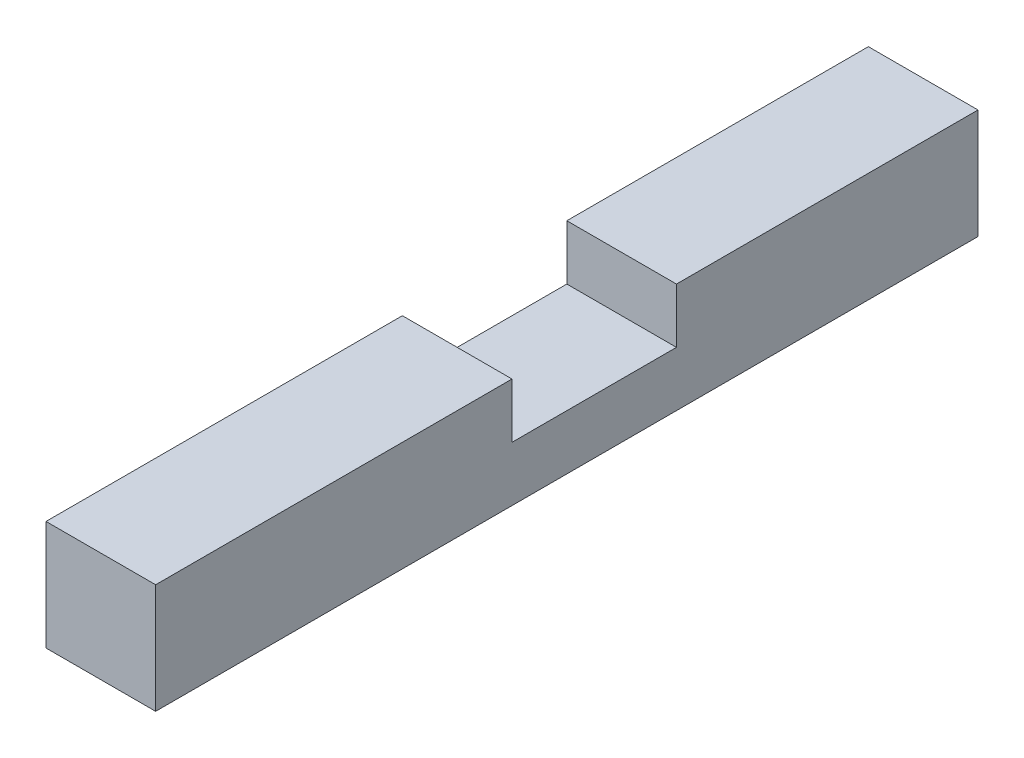
SolidWorks part; units mm, degrees
ref_plane "前基準面" through (0, 0, 0) normal (0, 0, 1) x (1, 0, 0)
ref_plane "上基準面" through (0, 0, 0) normal (0, 1, 0) x (1, 0, 0)
ref_plane "右基準面" through (0, 0, 0) normal (1, 0, 0) x (0, 0, -1)
sketch "草圖1" plane through (0, 0, 0) normal (0, 0, 1) x (1, 0, 0)
  line L1 (-2, 2) -> (2, 2)
  line L2 (-2, 2) -> (-2, -2)
  line L3 (-2, -2) -> (2, -2)
  line L4 (2, 2) -> (2, -2)
  line L5 (-2, 2) -> (2, -2) construction
  line L6 (-2, -2) -> (2, 2) construction
  point P0 (0, 0)
extrude "填料-伸長1" add sketch "草圖1" along normal blind 30 contours L1 L4 L3 L2
sketch "草圖3" plane through (-2, 0, 0) normal (-1, 0, 0) x (0, 0, 1)
  line L0 (30, -2) -> (0, -2) construction
  line L1 (0, 2) -> (11, 2)
  line L2 (0, 2) -> (0, -2)
  line L3 (0, -2) -> (11, -2)
  line L4 (11, 2) -> (11, -2)
sketch "草圖4" plane through (-2, 0, 0) normal (-1, 0, 0) x (0, 0, 1)
  line L1 (11, 2) -> (17, 2)
  line L2 (11, 2) -> (11, 0)
  line L3 (11, 0) -> (17, 0)
  line L4 (17, 2) -> (17, 0)
extrude "除料-伸長1" cut sketch "草圖4" against normal blind 4
